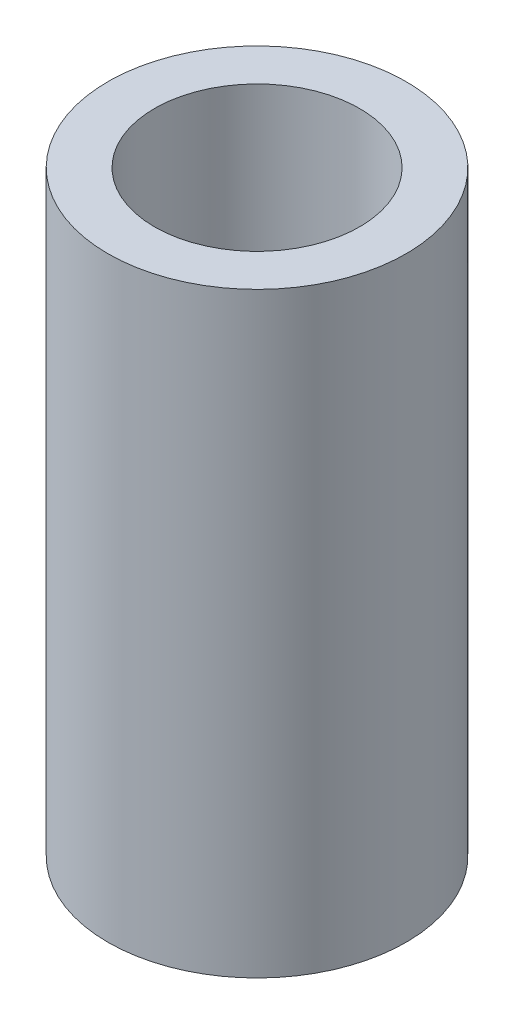
SolidWorks part; units mm, degrees
ref_plane "Front Plane" through (0, 0, 0) normal (0, 0, 1) x (1, 0, 0)
ref_plane "Top Plane" through (0, 0, 0) normal (0, 1, 0) x (1, 0, 0)
ref_plane "Right Plane" through (0, 0, 0) normal (1, 0, 0) x (0, 0, -1)
sketch "Sketch1" plane through (0, 0, 0) normal (0, 1, 0) x (1, 0, 0)
  circle A0 centre (0, 0) radius 1.5875
  dimension "D1" = 3.175
extrude "Boss-Extrude1" add sketch "Sketch1" along normal blind 6.35
hole_wizard "#2-56 Tapped Hole1" positions "Sketch3" profile "Sketch4" tap size "#2-56" standard "ANSI Inch" end condition through all
sketch "Sketch3" plane through (0, 6.35, 0) normal (0, 1, 0) x (1, 0, 0)
  point P0 (0, 0)
sketch "Sketch4" plane through (0, 6.35, 0) normal (1, 0, 0) x (0, 0, 1)
  line L0 (0, 0) -> (0, 6.35)
  line L1 (0, 6.35) -> (1.0922, 6.35)
  line L2 (1.0922, 6.35) -> (1.0922, 0)
  line L5 (1.0922, 0) -> (0, 0)
  line L11 (0, -6.35) -> (0, 107.95) construction
  dimension "Thread Major Dia." = 2.1844
  dimension "Thru Tap Drill Depth" = 6.35
